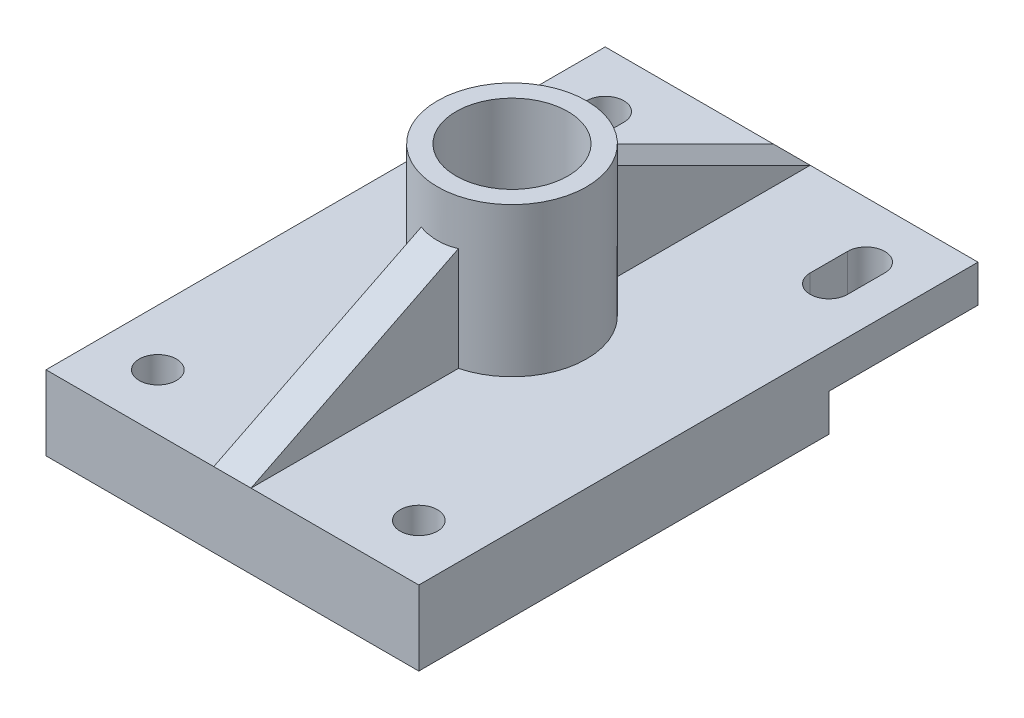
SolidWorks part; units mm, degrees
ref_plane "Спереди" through (0, 0, 0) normal (0, 0, 1) x (1, 0, 0)
ref_plane "Сверху" through (0, 0, 0) normal (0, 1, 0) x (1, 0, 0)
ref_plane "Справа" through (0, 0, 0) normal (1, 0, 0) x (0, 0, -1)
sketch "Эскиз2" plane through (0, 0, 0) normal (0, 1, 0) x (1, 0, 0)
  line L1 (-50, -75) -> (50, -75)
  line L2 (-50, -75) -> (-50, 75)
  line L3 (-50, 75) -> (50, 75)
  line L4 (50, -75) -> (50, 75)
  line L5 (-50, -75) -> (50, 75) construction
  line L6 (-50, 75) -> (50, -75) construction
  point P1 (0, 0)
  dimension "D1" = 100
  dimension "D2" = 150
extrude "Бобышка-Вытянуть2" add sketch "Эскиз2" against normal blind 20
sketch "Эскиз3" plane through (50, 0, 0) normal (1, 0, 0) x (0, 0, -1)
  line L0 (35, -20) -> (35, -10)
  line L1 (-75, -20) -> (75, -20) construction
  line L2 (35, -10) -> (75, -10)
  line L3 (75, -20) -> (75, 0) construction
  line L4 (35, -20) -> (75, -20)
  line L5 (75, -20) -> (75, -10)
  dimension "D1" = 40
  dimension "D2" = 10
extrude "Вырез-Вытянуть1" cut sketch "Эскиз3" against normal through all contours L5 L2 L0 L4
sketch "Эскиз5" plane through (0, 0, 0) normal (0, 1, 0) x (1, 0, 0)
  line L0 (-35, 60) -> (-35, 50) construction
  line L1 (-30, 60) -> (-30, 50)
  line L2 (-40, 60) -> (-40, 50)
  line L3 (50, 75) -> (-50, 75) construction
  line L4 (-50, 75) -> (-50, -75) construction
  line L5 (-50, -75) -> (50, -75) construction
  arc A0 (-30, 60) -> (-40, 60) centre (-35, 60) ccw
  arc A1 (-40, 50) -> (-30, 50) centre (-35, 50) ccw
  circle A2 centre (-35, -60) radius 5
  point P2 (-35, 55)
  point P15 (-35, 45)
  point P16 (-35, 65)
  dimension "D5" = 10
  dimension "D7" = 20
  dimension "D1" = 15
  dimension "D2" = 15
  dimension "D3" = 15
  dimension "D4" = 15
  dimension "D6" = 10
extrude "Вырез-Вытянуть3" cut sketch "Эскиз5" against normal through all
mirror "Зеркальное отражение2" about plane through (0, 0, 0) normal (1, 0, 0) of "Вырез-Вытянуть3"
sketch "Эскиз6" plane through (0, 0, 0) normal (0, 1, 0) x (1, 0, 0)
  circle A0 centre (0, 0) radius 20
  circle A1 centre (0, 0) radius 15
  dimension "D1" = 40
  dimension "D2" = 30
extrude "Бобышка-Вытянуть6" add sketch "Эскиз6" along normal blind 40
sketch "Эскиз7" plane through (0, 0, 0) normal (1, 0, 0) x (0, 0, -1)
  line L0 (-75, 0) -> (-15, 30)
  line L1 (-15, 30) -> (-15, 0)
  line L2 (-75, 0) -> (75, 0) construction
  line L3 (-75, 0) -> (-15, 0)
  line L4 (-15, 40) -> (-15, 0) construction
  point P3 (0, 0)
  dimension "D1" = 30
extrude "Бобышка-Вытянуть9" add sketch "Эскиз7" along normal mid plane 10 contours L1 L3 L0
mirror "Зеркальное отражение3" about plane through (0, 0, 0) normal (0, 0, 1) of "Бобышка-Вытянуть9"
sketch "Эскиз4" plane through (0, 0, 0) normal (0, 1, 0) x (1, 0, 0)
  line L0 (-35, 60) -> (-35, 50) construction
  line L1 (-30, 60) -> (-30, 50)
  line L2 (-40, 60) -> (-40, 50)
  line L3 (0, 75) -> (0, -75) construction
  line L4 (50, 75) -> (-50, 75) construction
  line L5 (-50, -75) -> (50, -75) construction
  line L7 (-50, 0) -> (50, 0) construction
  line L8 (-50, 75) -> (-50, -75) construction
  line L9 (50, -75) -> (50, 75) construction
  arc A0 (-30, 60) -> (-40, 60) centre (-35, 60) ccw
  arc A1 (-40, 50) -> (-30, 50) centre (-35, 50) ccw
  circle A2 centre (-35, -60) radius 5
  point P2 (-35, 55)
  point P11 (-35, 45)
  point P12 (-35, 65)
  point P13 (0, 0)
  dimension "D1" = 20
  dimension "D5" = 10
  dimension "D2" = 10
  dimension "D3" = 15
  dimension "D4" = 15
  dimension "D6" = 15
  dimension "D7" = 15
extrude "Вырез-Вытянуть2" cut sketch "Эскиз4" against normal through all contours L2 A1 L1 A0
